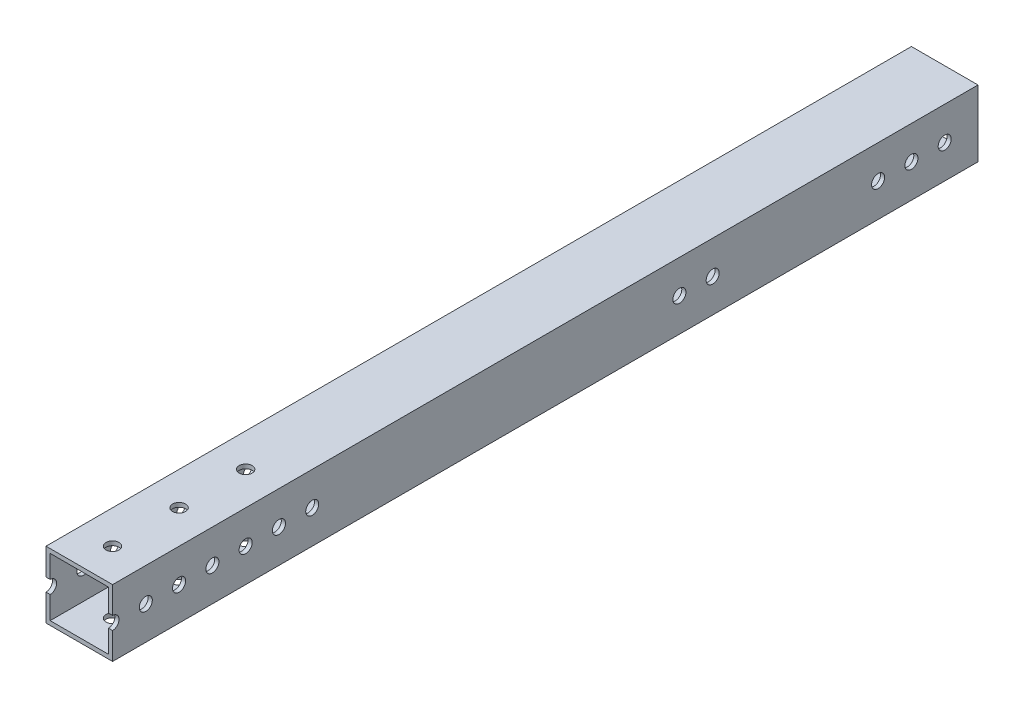
SolidWorks part; units mm, degrees
material "6061-T6 (SS)"
ref_plane "Front Plane" through (0, 0, 0) normal (0, 0, 1) x (1, 0, 0)
ref_plane "Top Plane" through (0, 0, 0) normal (0, 1, 0) x (1, 0, 0)
ref_plane "Right Plane" through (0, 0, 0) normal (1, 0, 0) x (0, 0, -1)
sketch "Sketch1" plane through (0, 0, 0) normal (0, 0, 1) x (1, 0, 0)
  line L0 (1.5875, 23.8125) -> (23.8125, 23.8125)
  line L1 (0, 0) -> (25.4, 0)
  line L2 (0, 0) -> (0, 25.4)
  line L3 (0, 25.4) -> (25.4, 25.4)
  line L4 (25.4, 0) -> (25.4, 25.4)
  line L5 (23.8125, 1.5875) -> (23.8125, 23.8125)
  line L6 (1.5875, 1.5875) -> (23.8125, 1.5875)
  line L7 (1.5875, 1.5875) -> (1.5875, 23.8125)
  dimension "D1" = 25.4
  dimension "D2" = 25.4
  dimension "D3" = 1.5875
extrude "Boss-Extrude1" add sketch "Sketch1" along normal blind 1016
sketch "Sketch2" plane through (0, 0, 0) normal (0, -1, 0) x (-1, 0, 0)
  line L1 (-25.4, -1016) -> (-25.4, 0) construction
  line L2 (0, -1016) -> (-25.4, -1016) construction
  circle A0 centre (12.7, -1003.3) radius 2.4892
  circle A1 centre (-12.7, -1003.3) radius 2.4892
  circle A2 centre (-12.7, -977.9) radius 2.4892
  circle A3 centre (-12.7, -952.5) radius 2.4892
  circle A4 centre (-12.7, -927.1) radius 2.4892
  circle A5 centre (-12.7, -901.7) radius 2.4892
  circle A6 centre (-12.7, -876.3) radius 2.4892
  circle A7 centre (-12.7, -850.9) radius 2.4892
  circle A8 centre (-12.7, -825.5) radius 2.4892
  circle A9 centre (-12.7, -800.1) radius 2.4892
  circle A10 centre (-12.7, -774.7) radius 2.4892
  circle A11 centre (-12.7, -749.3) radius 2.4892
  circle A12 centre (-12.7, -723.9) radius 2.4892
  circle A13 centre (12.7, -977.9) radius 2.4892
  circle A14 centre (12.7, -952.5) radius 2.4892
  circle A15 centre (12.7, -927.1) radius 2.4892
  circle A16 centre (12.7, -901.7) radius 2.4892
  circle A17 centre (12.7, -876.3) radius 2.4892
  circle A18 centre (12.7, -850.9) radius 2.4892
  circle A19 centre (12.7, -825.5) radius 2.4892
  circle A20 centre (12.7, -800.1) radius 2.4892
  circle A21 centre (12.7, -774.7) radius 2.4892
  circle A22 centre (12.7, -749.3) radius 2.4892
  circle A23 centre (12.7, -723.9) radius 2.4892
  circle A24 centre (12.7, -698.5) radius 2.4892
  circle A25 centre (-12.7, -698.5) radius 2.4892
  circle A26 centre (12.7, -673.1) radius 2.4892
  circle A27 centre (-12.7, -673.1) radius 2.4892
  circle A28 centre (12.7, -647.7) radius 2.4892
  circle A29 centre (-12.7, -647.7) radius 2.4892
  circle A30 centre (12.7, -622.3) radius 2.4892
  circle A31 centre (-12.7, -622.3) radius 2.4892
  circle A32 centre (12.7, -596.9) radius 2.4892
  circle A33 centre (-12.7, -596.9) radius 2.4892
  circle A34 centre (12.7, -571.5) radius 2.4892
  circle A35 centre (-12.7, -571.5) radius 2.4892
  circle A36 centre (12.7, -546.1) radius 2.4892
  circle A37 centre (-12.7, -546.1) radius 2.4892
  circle A38 centre (12.7, -520.7) radius 2.4892
  circle A39 centre (-12.7, -520.7) radius 2.4892
  circle A40 centre (12.7, -495.3) radius 2.4892
  circle A41 centre (-12.7, -495.3) radius 2.4892
  circle A42 centre (12.7, -469.9) radius 2.4892
  circle A43 centre (-12.7, -469.9) radius 2.4892
  circle A44 centre (12.7, -444.5) radius 2.4892
  circle A45 centre (-12.7, -444.5) radius 2.4892
  circle A46 centre (12.7, -419.1) radius 2.4892
  circle A47 centre (-12.7, -419.1) radius 2.4892
  circle A48 centre (12.7, -393.7) radius 2.4892
  circle A49 centre (-12.7, -393.7) radius 2.4892
  circle A50 centre (12.7, -368.3) radius 2.4892
  circle A51 centre (-12.7, -368.3) radius 2.4892
  circle A52 centre (12.7, -342.9) radius 2.4892
  circle A53 centre (-12.7, -342.9) radius 2.4892
  circle A54 centre (12.7, -317.5) radius 2.4892
  circle A55 centre (-12.7, -317.5) radius 2.4892
  circle A56 centre (12.7, -292.1) radius 2.4892
  circle A57 centre (-12.7, -292.1) radius 2.4892
  circle A58 centre (12.7, -266.7) radius 2.4892
  circle A59 centre (-12.7, -266.7) radius 2.4892
  dimension "D1" = 2
  dimension "D3" = 4.9784
  dimension "D4" = 12.7
  dimension "D5" = 25.4
  dimension "D6" = 25.4
  dimension "D7" = 12.7
  dimension "D2" = 30
extrude "Cut-Extrude1" cut sketch "Sketch2" against normal through all
sketch "Sketch4" plane through (25.4, 0, 0) normal (1, 0, 0) x (0, 0, -1)
  line L0 (-1016, 0) -> (-1016, 25.4) construction
  line L1 (-1016, 0) -> (0, 0) construction
  line L2 (0, 0) -> (0, 25.4) construction
  circle A0 centre (-1003.3, 12.7) radius 2.4892
  circle A27 centre (-990.6, 12.7) radius 2.4892
  circle A28 centre (-977.9, 12.7) radius 2.4892
  circle A29 centre (-965.2, 12.7) radius 2.4892
  circle A30 centre (-952.5, 12.7) radius 2.4892
  circle A31 centre (-939.8, 12.7) radius 2.4892
  circle A32 centre (-927.1, 12.7) radius 2.4892
  circle A33 centre (-914.4, 12.7) radius 2.4892
  circle A34 centre (-901.7, 12.7) radius 2.4892
  circle A35 centre (-889, 12.7) radius 2.4892
  circle A36 centre (-876.3, 12.7) radius 2.4892
  circle A37 centre (-863.6, 12.7) radius 2.4892
  circle A38 centre (-850.9, 12.7) radius 2.4892
  circle A39 centre (-838.2, 12.7) radius 2.4892
  circle A40 centre (-825.5, 12.7) radius 2.4892
  circle A41 centre (-812.8, 12.7) radius 2.4892
  circle A42 centre (-800.1, 12.7) radius 2.4892
  circle A43 centre (-787.4, 12.7) radius 2.4892
  circle A44 centre (-774.7, 12.7) radius 2.4892
  circle A45 centre (-762, 12.7) radius 2.4892
  circle A46 centre (-749.3, 12.7) radius 2.4892
  circle A47 centre (-736.6, 12.7) radius 2.4892
  circle A48 centre (-723.9, 12.7) radius 2.4892
  circle A49 centre (-711.2, 12.7) radius 2.4892
  circle A50 centre (-698.5, 12.7) radius 2.4892
  circle A51 centre (-685.8, 12.7) radius 2.4892
  circle A52 centre (-673.1, 12.7) radius 2.4892
  circle A53 centre (-660.4, 12.7) radius 2.4892
  circle A54 centre (-647.7, 12.7) radius 2.4892
  circle A55 centre (-635, 12.7) radius 2.4892
  circle A56 centre (-622.3, 12.7) radius 2.4892
  circle A57 centre (-609.6, 12.7) radius 2.4892
  circle A58 centre (-596.9, 12.7) radius 2.4892
  circle A65 centre (-113.9147, 12.7) radius 2.4892
  circle A66 centre (-101.2147, 12.7) radius 2.4892
  circle A67 centre (-584.2, 12.7) radius 2.4892
  circle A68 centre (-571.5, 12.7) radius 2.4892
  circle A69 centre (-558.8, 12.7) radius 2.4892
  circle A70 centre (-546.1, 12.7) radius 2.4892
  circle A71 centre (-533.4, 12.7) radius 2.4892
  circle A72 centre (-520.7, 12.7) radius 2.4892
  circle A73 centre (-508, 12.7) radius 2.4892
  circle A74 centre (-495.3, 12.7) radius 2.4892
  circle A75 centre (-482.6, 12.7) radius 2.4892
  circle A76 centre (-469.9, 12.7) radius 2.4892
  circle A77 centre (-457.2, 12.7) radius 2.4892
  circle A78 centre (-444.5, 12.7) radius 2.4892
  circle A79 centre (-431.8, 12.7) radius 2.4892
  circle A80 centre (-419.1, 12.7) radius 2.4892
  circle A81 centre (-406.4, 12.7) radius 2.4892
  circle A82 centre (-393.7, 12.7) radius 2.4892
  circle A83 centre (-381, 12.7) radius 2.4892
  circle A84 centre (-368.3, 12.7) radius 2.4892
  circle A85 centre (-355.6, 12.7) radius 2.4892
  circle A86 centre (-342.9, 12.7) radius 2.4892
  circle A87 centre (-330.2, 12.7) radius 2.4892
  circle A88 centre (-317.5, 12.7) radius 2.4892
  circle A89 centre (-304.8, 12.7) radius 2.4892
  circle A90 centre (-292.1, 12.7) radius 2.4892
  circle A91 centre (-279.4, 12.7) radius 2.4892
  circle A92 centre (-266.7, 12.7) radius 2.4892
  circle A93 centre (-254, 12.7) radius 2.4892
  circle A94 centre (-12.7, 12.7) radius 2.4892
  circle A95 centre (-25.4, 12.7) radius 2.4892
  circle A96 centre (-38.1, 12.7) radius 2.4892
  dimension "D1" = 60
  dimension "D2" = 4.9784
  dimension "D3" = 12.7
  dimension "D4" = 12.7
  dimension "D6" = 12.7
  dimension "D7" = 12.7
  dimension "D5" = 101.2147
  dimension "D10" = 12.7
  dimension "D8" = 12.7
  dimension "D9" = 12.7
  dimension "D11" = 12.7
extrude "Cut-Extrude2" cut sketch "Sketch4" against normal through all
sketch "Sketch5" plane through (0, 25.4, 0) normal (0, 1, 0) x (1, 0, 0)
  line L0 (25.4, -1016) -> (25.4, 0) construction
  line L1 (25.4, -330.1728) -> (0, -330.1728)
  line L2 (25.4, -330.1728) -> (25.4, -1016)
  line L3 (25.4, -1016) -> (0, -1016)
  line L4 (0, -330.1728) -> (0, -1016)
extrude "Cut-Extrude3" cut sketch "Sketch5" against normal through all
